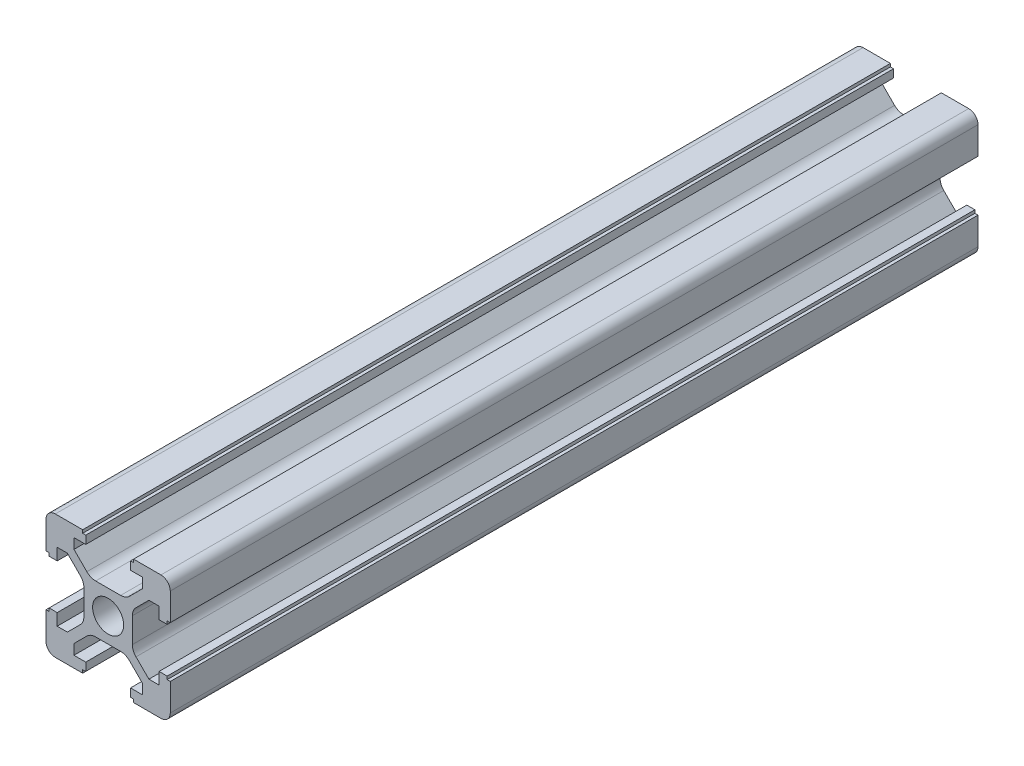
SolidWorks part; units mm, degrees
material "6063-O"
ref_plane "Front Plane" through (0, 0, 0) normal (0, 0, 1) x (1, 0, 0)
ref_plane "Top Plane" through (0, 0, 0) normal (0, 1, 0) x (1, 0, 0)
ref_plane "Right Plane" through (0, 0, 0) normal (1, 0, 0) x (0, 0, -1)
sketch "Sketch1" plane through (0, 0, 0) normal (0, 0, 1) x (1, 0, 0)
  line L0 (10, -4.1) -> (10, -8.5)
  line L1 (4.1, 10) -> (8.5, 10)
  line L2 (8.5, -10) -> (4.1, -10)
  line L3 (-8.5, -10) -> (-4.1, -10)
  line L4 (10, 8.5) -> (10, 4.1)
  line L7 (8.5, 10) -> (4.1, 10)
  line L8 (5.5, 6.5607) -> (3.4251, 4.4858)
  line L9 (8.5, 10) -> (4.1, 10)
  line L10 (3.9, 2.0109) -> (3.9, -2.0109)
  line L11 (2.0109, -3.9) -> (-2.0109, -3.9)
  line L12 (-3.9, -2.0109) -> (-3.9, 2.0109)
  line L13 (-2.0109, 3.9) -> (2.8393, 3.9)
  line L14 (2.5, 0) -> (22.2403, 0) construction
  line L15 (3.6, 9.5) -> (3.6, 8.2)
  line L16 (9.5, 3.6) -> (8.2, 3.6)
  line L17 (8.2, 3.6) -> (8.2, 5.5)
  line L18 (8.2, 5.5) -> (6.5607, 5.5)
  line L19 (10, -4.1) -> (10, -8.5)
  line L20 (4.1, 9.5) -> (3.6, 9.5)
  line L21 (4.1, 10) -> (4.1, 9.5)
  line L22 (8.5, 10) -> (4.1, 10)
  line L23 (10, 4.1) -> (9.5, 4.1)
  line L24 (9.5, 4.1) -> (9.5, 3.6)
  line L25 (5.5, 8.2) -> (5.5, 6.5607)
  line L26 (3.6, 8.2) -> (5.5, 8.2)
  line L27 (4.4858, 3.4251) -> (6.5607, 5.5)
  line L28 (10, -8.5) -> (10, -4.1)
  line L29 (6.5607, -5.5) -> (4.4858, -3.4251)
  line L30 (10, -8.5) -> (10, -4.1)
  line L31 (2.0109, -3.9) -> (-2.0109, -3.9)
  line L32 (3.9, 2.8393) -> (3.9, -2.0109)
  line L33 (9.5, -3.6) -> (8.2, -3.6)
  line L34 (3.6, -9.5) -> (3.6, -8.2)
  line L35 (3.6, -8.2) -> (5.5, -8.2)
  line L36 (5.5, -8.2) -> (5.5, -6.5607)
  line L37 (9.5, -4.1) -> (9.5, -3.6)
  line L38 (10, -4.1) -> (9.5, -4.1)
  line L39 (10, -8.5) -> (10, -4.1)
  line L40 (4.1, -10) -> (4.1, -9.5)
  line L41 (4.1, -9.5) -> (3.6, -9.5)
  line L42 (8.2, -5.5) -> (6.5607, -5.5)
  line L43 (8.2, -3.6) -> (8.2, -5.5)
  line L44 (3.4251, -4.4858) -> (5.5, -6.5607)
  line L45 (-4.1, -10) -> (-8.5, -10)
  line L46 (-10, -8.5) -> (-10, -4.1)
  line L47 (-8.5, -10) -> (-4.1, -10)
  line L48 (-5.5, -6.5607) -> (-3.4251, -4.4858)
  line L49 (-8.5, -10) -> (-4.1, -10)
  line L50 (-3.9, -2.0109) -> (-3.9, 2.0109)
  line L51 (2.0109, -3.9) -> (-2.0109, -3.9)
  line L52 (-3.6, -9.5) -> (-3.6, -8.2)
  line L53 (-9.5, -3.6) -> (-8.2, -3.6)
  line L54 (-8.2, -3.6) -> (-8.2, -5.5)
  line L55 (-8.2, -5.5) -> (-6.5607, -5.5)
  line L56 (-4.1, -9.5) -> (-3.6, -9.5)
  line L57 (-4.1, -10) -> (-4.1, -9.5)
  line L58 (-8.5, -10) -> (-4.1, -10)
  line L59 (-10, -4.1) -> (-9.5, -4.1)
  line L60 (-9.5, -4.1) -> (-9.5, -3.6)
  line L61 (-5.5, -8.2) -> (-5.5, -6.5607)
  line L62 (-3.6, -8.2) -> (-5.5, -8.2)
  line L63 (-4.4858, -3.4251) -> (-6.5607, -5.5)
  line L64 (-10, 4.1) -> (-10, 8.5)
  line L65 (-8.5, 10) -> (-4.1, 10)
  line L66 (-10, 8.5) -> (-10, 4.1)
  line L67 (-6.5607, 5.5) -> (-4.4858, 3.4251)
  line L68 (-10, 8.5) -> (-10, 4.1)
  line L69 (-2.0109, 3.9) -> (2.0109, 3.9)
  line L70 (-3.9, -2.0109) -> (-3.9, 2.0109)
  line L71 (-9.5, 3.6) -> (-8.2, 3.6)
  line L72 (-3.6, 9.5) -> (-3.6, 8.2)
  line L73 (-3.6, 8.2) -> (-5.5, 8.2)
  line L74 (-5.5, 8.2) -> (-5.5, 6.5607)
  line L75 (-9.5, 4.1) -> (-9.5, 3.6)
  line L76 (-10, 4.1) -> (-9.5, 4.1)
  line L77 (-10, 8.5) -> (-10, 4.1)
  line L78 (-4.1, 10) -> (-4.1, 9.5)
  line L79 (-4.1, 9.5) -> (-3.6, 9.5)
  line L80 (-8.2, 5.5) -> (-6.5607, 5.5)
  line L81 (-8.2, 3.6) -> (-8.2, 5.5)
  line L82 (-3.4251, 4.4858) -> (-5.5, 6.5607)
  line L83 (4.1, -10) -> (8.5, -10)
  arc A0 (2.0109, -3.9) -> (3.4251, -4.4858) centre (2.0109, -5.9) cw
  arc A1 (4.4858, -3.4251) -> (3.9, -2.0109) centre (5.9, -2.0109) cw
  arc A2 (3.9, 2.0109) -> (4.4858, 3.4251) centre (5.9, 2.0109) cw
  arc A3 (2.0109, 3.9) -> (3.4251, 4.4858) centre (2.0109, 5.9) ccw
  arc A4 (-2.0109, 3.9) -> (-3.4251, 4.4858) centre (-2.0109, 5.9) cw
  arc A5 (-4.4858, 3.4251) -> (-3.9, 2.0109) centre (-5.9, 2.0109) cw
  arc A6 (-3.4251, -4.4858) -> (-2.0109, -3.9) centre (-2.0109, -5.9) cw
  arc A7 (-3.9, -2.0109) -> (-4.4858, -3.4251) centre (-5.9, -2.0109) cw
  circle A8 centre (0, 0) radius 2.5
  arc A9 (-8.5, -10) -> (-10, -8.5) centre (-8.5, -8.5) cw
  arc A10 (-10, 8.5) -> (-8.5, 10) centre (-8.5, 8.5) cw
  arc A11 (8.5, 10) -> (10, 8.5) centre (8.5, 8.5) cw
  arc A12 (8.5, -10) -> (10, -8.5) centre (8.5, -8.5) ccw
  point P0 (0, 0)
  point P86 (0, 0)
  point P107 (10, -10)
  dimension "D3" = 2
  dimension "D5" = 5
  dimension "D2" = 1.5
  dimension "D8" = 1.5
  dimension "D6" = 4
  dimension "D7" = 6.1
  dimension "D11" = 0.5
  dimension "D12" = 0.5
extrude "Boss-Extrude2" add sketch "Sketch1" along normal blind 130
